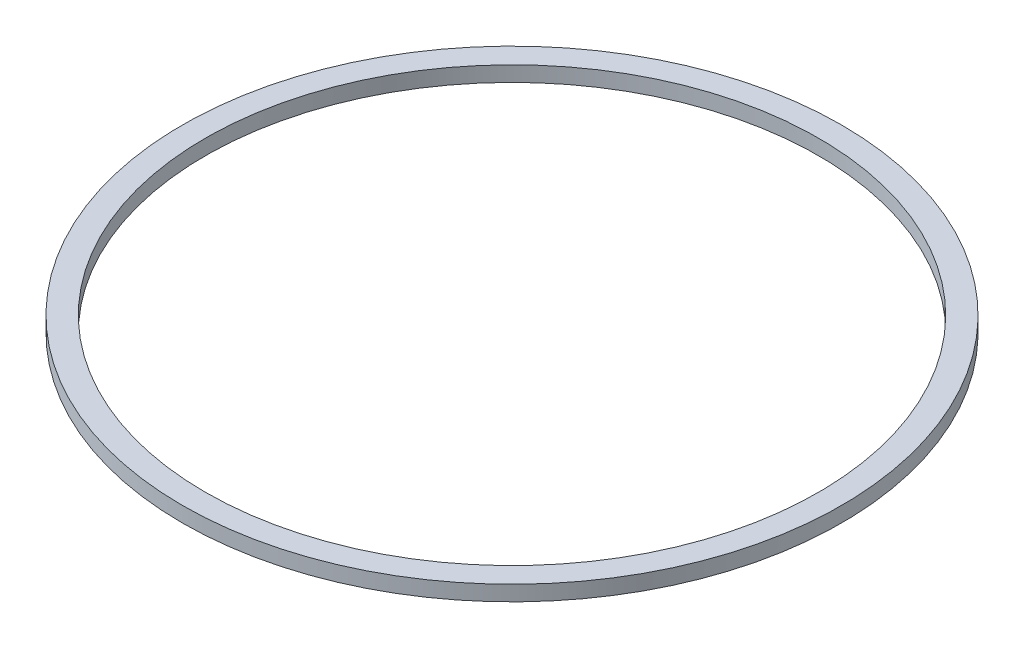
SolidWorks part; units mm, degrees
ref_plane "Front Plane" through (0, 0, 0) normal (0, 0, 1) x (1, 0, 0)
ref_plane "Top Plane" through (0, 0, 0) normal (0, 1, 0) x (1, 0, 0)
ref_plane "Right Plane" through (0, 0, 0) normal (1, 0, 0) x (0, 0, -1)
sketch "Sketch1" plane through (0, 0, 0) normal (0, 1, 0) x (1, 0, 0)
  circle A0 centre (0, 0) radius 40.2
  circle A2 centre (0, 0) radius 43.2
  dimension "D1" = 3
extrude "Boss-Extrude1" add sketch "Sketch1" along normal blind 2
